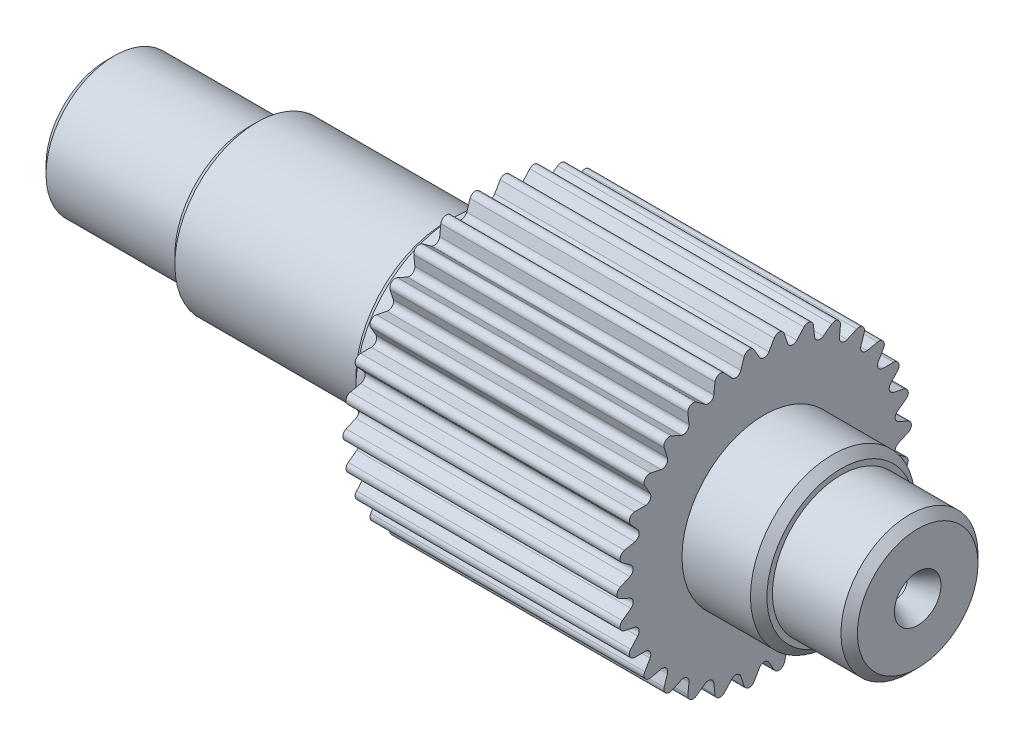
SolidWorks part; units mm, degrees
ref_plane "Спереди" through (0, 0, 0) normal (0, 0, 1) x (1, 0, 0)
ref_plane "Сверху" through (0, 0, 0) normal (0, 1, 0) x (1, 0, 0)
ref_plane "Справа" through (0, 0, 0) normal (1, 0, 0) x (0, 0, -1)
sketch "Эскиз1" plane through (0, 0, 0) normal (0, 0, 1) x (1, 0, 0)
  line L0 (0, -12.5) -> (26, -12.5)
  line L1 (0, 0) -> (148, 0)
  line L2 (0, 0) -> (0, -12.5)
  line L4 (148, 0) -> (148, -12.5)
  line L5 (26, -12.5) -> (26, -15)
  line L6 (26, -15) -> (62, -15)
  line L7 (62, -15) -> (62, -18)
  line L8 (62, -18) -> (70, -18)
  line L9 (70, -18) -> (70, -28.8)
  line L10 (70, -28.8) -> (120, -28.8)
  line L11 (120, -28.8) -> (120, -15)
  line L12 (120, -15) -> (134, -15)
  line L13 (134, -15) -> (134, -12.5)
  line L14 (134, -12.5) -> (148, -12.5)
  point P18 (0, 0)
  point P20 (0.8738, 4.1592)
  point P21 (0, 4.1592)
  point P22 (-25.8028, 8.7489)
  dimension "D1" = 148
  dimension "D2" = 26
  dimension "D3" = 36
  dimension "D4" = 8
  dimension "D5" = 50
  dimension "D6" = 14
  dimension "D7" = 14
  dimension "D8" = 12.5
  dimension "D9" = 15
  dimension "D10" = 18
  dimension "D11" = 28.8
  dimension "D12" = 15
  dimension "D13" = 12.5
revolve "Повернуть1" add sketch "Эскиз1" angle 360 about L1
sketch "Эскиз2" plane through (0, 0, 0) normal (0, 0, 1) x (1, 0, 0)
  line L0 (0, 0) -> (46.5998, 0) construction
  line L1 (0, 4.25) -> (3.9, 2)
  line L2 (0, 12.5) -> (0, -12.5) construction
  line L3 (3.9, 2) -> (8.9, 2)
  line L4 (8.9, 2) -> (10.0547, 0)
  line L5 (0, 4.25) -> (0, 0)
  line L6 (0, 0) -> (10.0547, 0)
  dimension "D1" = 8.5
  dimension "D2" = 5
  dimension "D3" = 3.9
  dimension "D4" = 4
  dimension "D5" = 60
revolve "Вырез-Повернуть1" cut sketch "Эскиз2" angle 360 about L0
ref_plane "Плоскость4" through (74, 0, 0) normal (-1, 0, 0) x (0, 0, 1)
mirror "Зеркальное отражение1" about plane through (74, 0, 0) normal (-1, 0, 0) of "Вырез-Повернуть1"
sketch "Эскиз3" plane through (0, 0, 0) normal (0, 0, 1) x (1, 0, 0)
  line L0 (26, 0) -> (62, 0) construction
  line L1 (26, 12.5) -> (26, -12.5) construction
  line L2 (62, 18) -> (62, -18) construction
  line L3 (37, 0) -> (51, 0) construction
  line L4 (37, 4) -> (51, 4)
  line L5 (37, -4) -> (51, -4)
  arc A0 (37, 4) -> (37, -4) centre (37, 0) ccw
  arc A1 (51, -4) -> (51, 4) centre (51, 0) ccw
  point P8 (44, 0)
  dimension "D1" = 14
  dimension "D2" = 8
extrude "Вырез-Вытянуть1" cut sketch "Эскиз3" against normal through all from offset 10
sketch "Эскиз4" plane through (120, 0, 0) normal (1, 0, 0) x (0, 0, -1)
  line L0 (0, 0) -> (0, 39.314) construction
  line L1 (5, 31.6868) -> (-5, 31.6868)
  line L2 (-5, 31.6868) -> (0, 23.0265)
  line L3 (0, 23.0265) -> (5, 31.6868)
  circle A0 centre (0, 28.8) radius 2.8868 construction
  circle A1 centre (0, 0) radius 28.8 construction
  point P7 (0, 28.8)
  point P11 (0, 23.0265)
  point P12 (-5.5847, 31.684)
  point P13 (0, 0)
  dimension "D1" = 10
extrude "Вырез-Вытянуть2" cut sketch "Эскиз4" against normal through all
pattern_circular "Круговой массив1" count 30 over 360 about axis through (0, 0, 0) along (1, 0, 0) of "Вырез-Вытянуть2"
fillet "Скругление2" radius 1 60 edges at (95, 22.5233, -4.7875) (95, 21.0358, -9.3657) (95, 18.6288, -13.5346) (95, 21.0358, -18.9407) (95, 15.4077, -17.112) (95, 16.6381, -22.9004) (95, 11.5132, -19.9415) (95, 11.5132, -25.8592) (95, 7.1156, -21.8995) (95, 5.8852, -27.6878) (95, 2.4069, -22.9004) (95, 0, -28.3064) (95, -2.4069, -22.9004) (95, -5.8852, -27.6878) (95, -7.1156, -21.8995) (95, -11.5132, -25.8592) (95, -11.5132, -19.9415) (95, -16.6381, -22.9004) (95, -15.4077, -17.112) (95, -21.0358, -18.9407) (95, -18.6288, -13.5346) (95, -24.5141, -14.1532) (95, -21.0358, -9.3657) (95, -26.921, -8.7472) (95, -22.5233, -4.7875) (95, -28.1513, -2.9588) (95, -23.0265, 0) (95, -28.1513, 2.9588) (95, -22.5233, 4.7875) (95, -26.921, 8.7472) (95, -21.0358, 9.3657) (95, -24.5141, 14.1532) (95, -18.6288, 13.5346) (95, -21.0358, 18.9407) (95, -15.4077, 17.112) (95, -16.6381, 22.9004) (95, -11.5132, 19.9415) (95, -11.5132, 25.8592) (95, -7.1156, 21.8995) (95, -5.8852, 27.6878) (95, -2.4069, 22.9004) (95, 0, 28.3064) (95, 2.4069, 22.9004) (95, 5.8852, 27.6878) (95, 7.1156, 21.8995) (95, 11.5132, 25.8592) (95, 11.5132, 19.9415) (95, 16.6381, 22.9004) (95, 15.4077, 17.112) (95, 21.0358, 18.9407) (95, 18.6288, 13.5346) (95, 24.5141, 14.1532) (95, 21.0358, 9.3657) (95, 26.921, 8.7472) (95, 22.5233, 4.7875) (95, 28.1513, 2.9588) (95, 23.0265, 0) (95, 28.1513, -2.9588) (95, 26.921, -8.7472) (95, 24.5141, -14.1532)
chamfer "Фаска1" distance 1.5 angle 45 5 edges at (0, 0, 12.5) (26, 0, 15) (62, 0, 18) (134, 0, 15) (148, 0, 12.5)
